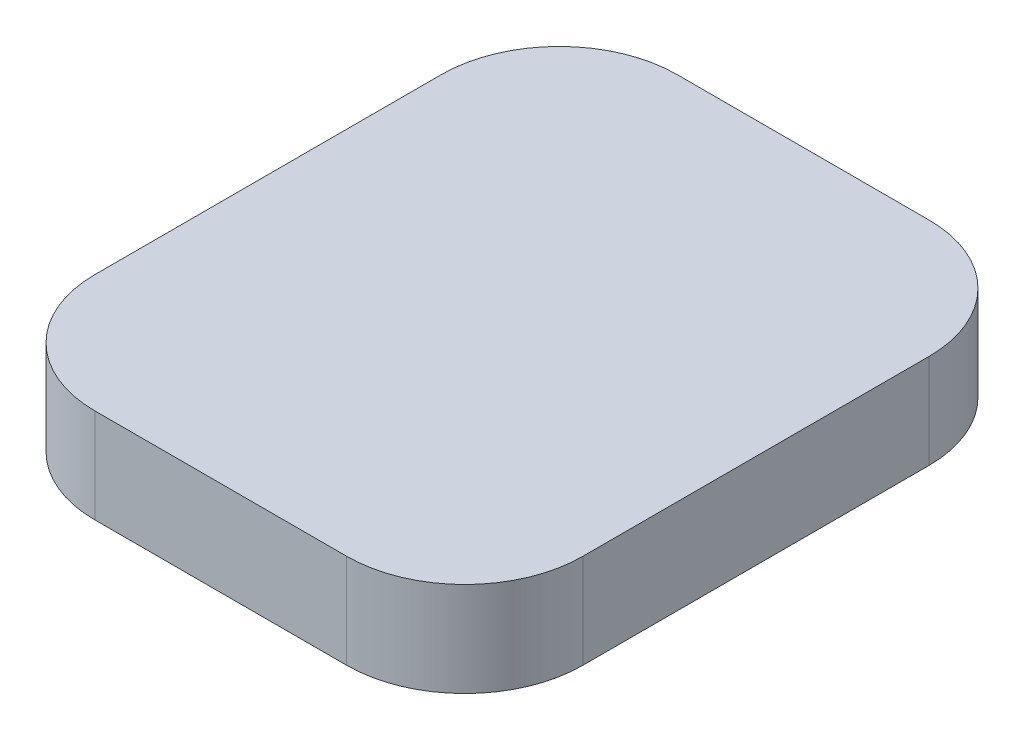
SolidWorks part; units mm, degrees
ref_plane "Front Plane" through (0, 0, 0) normal (0, 0, 1) x (1, 0, 0)
ref_plane "Top Plane" through (0, 0, 0) normal (0, 1, 0) x (1, 0, 0)
ref_plane "Right Plane" through (0, 0, 0) normal (1, 0, 0) x (0, 0, -1)
sketch "Sketch1" plane through (0, 0, 0) normal (0, 1, 0) x (1, 0, 0)
  line L0 (-4.5, 9.25) -> (3.5, 9.25)
  line L1 (-8.25, 5.5) -> (-8.25, -5.5)
  line L2 (-4.5, -9.25) -> (3.5, -9.25)
  line L3 (7.25, 5.5) -> (7.25, -5.5)
  arc A0 (3.5, 9.25) -> (7.25, 5.5) centre (3.5, 5.5) cw
  arc A1 (3.5, -9.25) -> (7.25, -5.5) centre (3.5, -5.5) ccw
  arc A2 (-4.5, -9.25) -> (-8.25, -5.5) centre (-4.5, -5.5) cw
  arc A3 (-8.25, 5.5) -> (-4.5, 9.25) centre (-4.5, 5.5) cw
  point P12 (-0.5, -9.25)
  dimension "D1" = 3.75
  dimension "D2" = 15.5
  dimension "D3" = 18.5
  dimension "D4" = 8.25
  dimension "D5" = 9.25
extrude "Boss-Extrude1" add sketch "Sketch1" along normal blind 3
